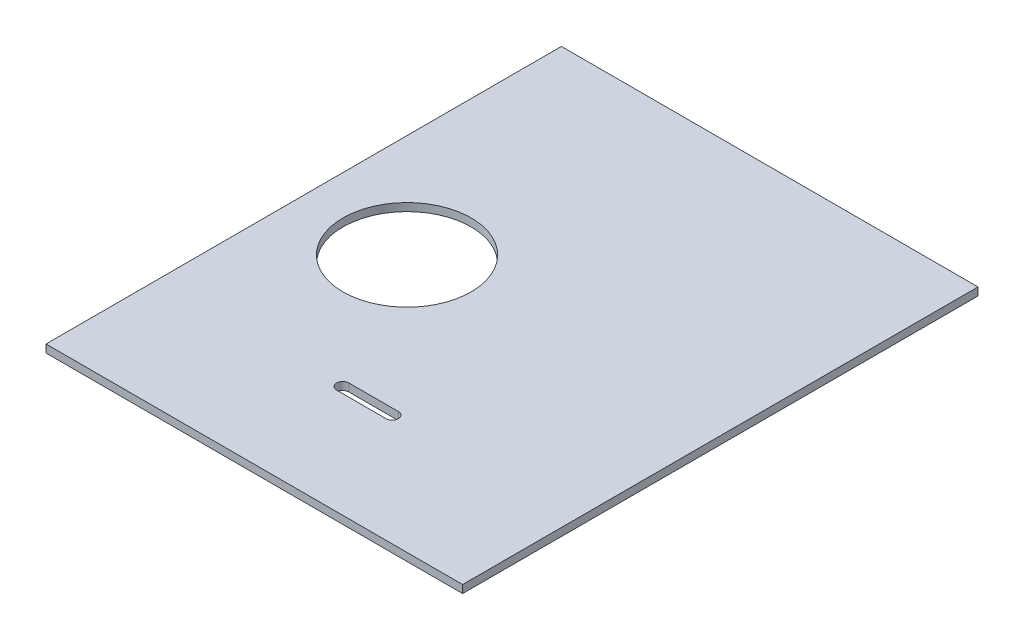
SolidWorks part; units mm, degrees
ref_plane "Front Plane" through (0, 0, 0) normal (0, 0, 1) x (1, 0, 0)
ref_plane "Top Plane" through (0, 0, 0) normal (0, 1, 0) x (1, 0, 0)
ref_plane "Right Plane" through (0, 0, 0) normal (1, 0, 0) x (0, 0, -1)
sketch "Sketch1" plane through (0, 0, 0) normal (0, 1, 0) x (1, 0, 0)
  line L1 (-84.325, -104.325) -> (84.325, -104.325)
  line L2 (-84.325, -104.325) -> (-84.325, 104.325)
  line L3 (-84.325, 104.325) -> (84.325, 104.325)
  line L4 (84.325, -104.325) -> (84.325, 104.325)
  line L5 (-84.325, -104.325) -> (84.325, 104.325) construction
  line L6 (-84.325, 104.325) -> (84.325, -104.325) construction
  point P1 (0, 0)
  dimension "D1" = 168.65
  dimension "D2" = 208.65
extrude "Boss-Extrude1" add sketch "Sketch1" along normal blind 3.18
sketch "Sketch2" plane through (0, 3.18, 0) normal (0, 1, 0) x (1, 0, 0)
  line L0 (-9.325, -59.175) -> (10.675, -59.175) construction
  line L1 (-84.325, -104.325) -> (84.325, -104.325) construction
  line L4 (10.675, -56.675) -> (-9.325, -56.675)
  line L5 (-9.325, -61.675) -> (10.675, -61.675)
  arc A4 (10.675, -61.675) -> (10.675, -56.675) centre (10.675, -59.175) ccw
  arc A5 (-9.325, -56.675) -> (-9.325, -61.675) centre (-9.325, -59.175) ccw
  dimension "D1" = 5
  dimension "D2" = 20
  dimension "D3" = 42.65
extrude "Cut-Extrude1" cut sketch "Sketch2" against normal up to next
sketch "Sketch3" [suppressed] plane through (0, 3.18, 0) normal (0, 1, 0) x (1, 0, 0)
  circle A1 centre (9.725, 44.3127) radius 1.6
  circle A2 centre (9.725, 44.3127) radius 1.6
  circle A3 centre (9.725, 72.2127) radius 1.6
  circle A4 centre (9.725, 72.2127) radius 1.6
  circle A5 centre (62.125, 77.3127) radius 1.6
  circle A6 centre (62.125, 77.3127) radius 1.6
  circle A7 centre (60.525, 29.0127) radius 1.6
  circle A8 centre (60.525, 29.0127) radius 1.6
  dimension "D2" = 0
  dimension "D3" = 0
  dimension "D4" = 0
  dimension "D5" = 0
extrude "Cut-Extrude2" [suppressed] cut sketch "Sketch3" against normal blind 3.18
sketch "Sketch5" [suppressed] plane through (0, 0, 0) normal (0, -1, 0) x (1, 0, 0)
sketch "Sketch36" [suppressed] plane through (0, 3.18, 0) normal (0, 1, 0) x (1, 0, 0)
  circle A1 centre (-31.975, 13.3425) radius 1.425
  circle A2 centre (-31.975, 13.3425) radius 1.425
  circle A3 centre (-8.125, 0) radius 1.425
  circle A4 centre (-8.125, 0) radius 1.425
  circle A5 centre (-55.825, 0) radius 1.425
  circle A6 centre (-55.825, 0) radius 1.425
  circle A7 centre (-31.975, -13.3425) radius 1.425
  circle A8 centre (-31.975, -13.3425) radius 1.425
  dimension "D1" = 0
  dimension "D2" = 0
  dimension "D4" = 0
  dimension "D5" = 0
sketch "Sketch37" [suppressed] plane through (0, 0, 0) normal (0, -1, 0) x (1, 0, 0)
  circle A1 centre (74.325, 94.325) radius 1.4224
  circle A2 centre (74.325, 94.325) radius 1.4224
  circle A3 centre (-74.325, -94.325) radius 1.4224
  circle A4 centre (-74.325, -94.325) radius 1.4224
  circle A5 centre (74.325, -94.325) radius 1.4224
  circle A6 centre (74.325, -94.325) radius 1.4224
  circle A7 centre (-74.325, 94.325) radius 1.4224
  circle A8 centre (-74.325, 94.325) radius 1.4224
  dimension "D1" = 0
  dimension "D2" = 0
  dimension "D3" = 0
  dimension "D4" = 0
extrude "Cut-Extrude19" [suppressed] cut sketch "Sketch37" against normal blind 3.18
sketch "Sketch40" [suppressed] plane through (-0.8952, 3.18, 70.2213) normal (0, 1, 0) x (1, 0, 0)
  line L0 (-83.4298, 174.5463) -> (-83.4298, -34.1037) construction
  line L1 (-48.4048, 33.7963) -> (50.1952, 33.7963)
  line L2 (-48.4048, 33.7963) -> (-48.4048, -28.1037)
  line L3 (-48.4048, -28.1037) -> (50.1952, -28.1037)
  line L4 (50.1952, 33.7963) -> (50.1952, -28.1037)
  line L5 (-48.4048, 33.7963) -> (50.1952, -28.1037) construction
  line L6 (-48.4048, -28.1037) -> (50.1952, 33.7963) construction
  line L10 (-83.4298, -34.1037) -> (85.2202, -34.1037) construction
  point P0 (0.8952, 2.8463)
  dimension "D1" = 35.025
  dimension "D2" = 6
  dimension "D3" = 98.6
  dimension "D4" = 61.9
extrude "Cut-Extrude20" [suppressed] cut sketch "Sketch40" against normal blind 10
fillet "Fillet1" [suppressed] radius 2.5
fillet "Fillet2" [suppressed] radius 2.5
fillet "Fillet3" [suppressed] radius 2.5
fillet "Fillet4" [suppressed] radius 2.5
sketch "Sketch42" [suppressed] plane through (-0.8952, 3.18, 70.2213) normal (0, 1, 0) x (1, 0, 0)
  line L0 (-45.9048, -28.1037) -> (47.6952, -28.1037) construction
  line L1 (-31.7548, -29.6537) -> (-23.7548, -29.6537)
  line L2 (-31.7548, -29.6537) -> (-31.7548, -28.1037)
  line L3 (-31.7548, -28.1037) -> (-23.7548, -28.1037)
  line L4 (-23.7548, -29.6537) -> (-23.7548, -28.1037)
  line L5 (-31.7548, -29.6537) -> (-23.7548, -28.1037) construction
  line L6 (-31.7548, -28.1037) -> (-23.7548, -29.6537) construction
  line L7 (-48.4048, 31.2963) -> (-48.4048, -25.6037) construction
  line L19 (50.1952, -25.6037) -> (50.1952, 31.2963) construction
  line L20 (24.6452, -28.1037) -> (32.6452, -28.1037)
  line L21 (24.6452, -28.1037) -> (24.6452, -29.6537)
  line L22 (24.6452, -29.6537) -> (32.6452, -29.6537)
  line L23 (32.6452, -28.1037) -> (32.6452, -29.6537)
  point P0 (-27.7548, -28.8787)
  dimension "D1" = 16.65
  dimension "D2" = 1.55
  dimension "D3" = 8
  dimension "D4" = 17.55
  dimension "D5" = 8
  dimension "D6" = 1.55
extrude "Cut-Extrude21" [suppressed] cut sketch "Sketch42" against normal blind 10
sketch "Sketch44" [suppressed] plane through (-0.8952, 3.18, 70.2213) normal (0, 1, 0) x (1, 0, 0)
  line L0 (47.6952, 33.7963) -> (-45.9048, 33.7963) construction
  line L1 (-27.2048, 33.7963) -> (-24.5048, 33.7963)
  line L2 (-27.2048, 33.7963) -> (-27.2048, 34.8463)
  line L3 (-27.2048, 34.8463) -> (-24.5048, 34.8463)
  line L4 (-24.5048, 33.7963) -> (-24.5048, 34.8463)
  line L5 (-48.4048, 31.2963) -> (-48.4048, -25.6037) construction
  line L6 (50.1952, -25.6037) -> (50.1952, 31.2963) construction
  line L7 (23.2452, 33.7963) -> (25.9452, 33.7963)
  line L8 (23.2452, 33.7963) -> (23.2452, 34.8463)
  line L9 (23.2452, 34.8463) -> (25.9452, 34.8463)
  line L10 (25.9452, 33.7963) -> (25.9452, 34.8463)
  dimension "D1" = 21.2
  dimension "D2" = 2.7
  dimension "D3" = 1.05
  dimension "D4" = 24.25
  dimension "D5" = 2.7
  dimension "D6" = 1.05
extrude "Cut-Extrude22" [suppressed] cut sketch "Sketch44" against normal blind 10
extrude "Cut-Extrude23" [suppressed] cut sketch "Sketch36" against normal up to next
sketch "Sketch45" plane through (0, 3.18, 0) normal (0, 1, 0) x (1, 0, 0)
  circle A0 centre (-42.4825, 0) radius 25.9511
extrude "Cut-Extrude24" cut sketch "Sketch45" against normal up to next
